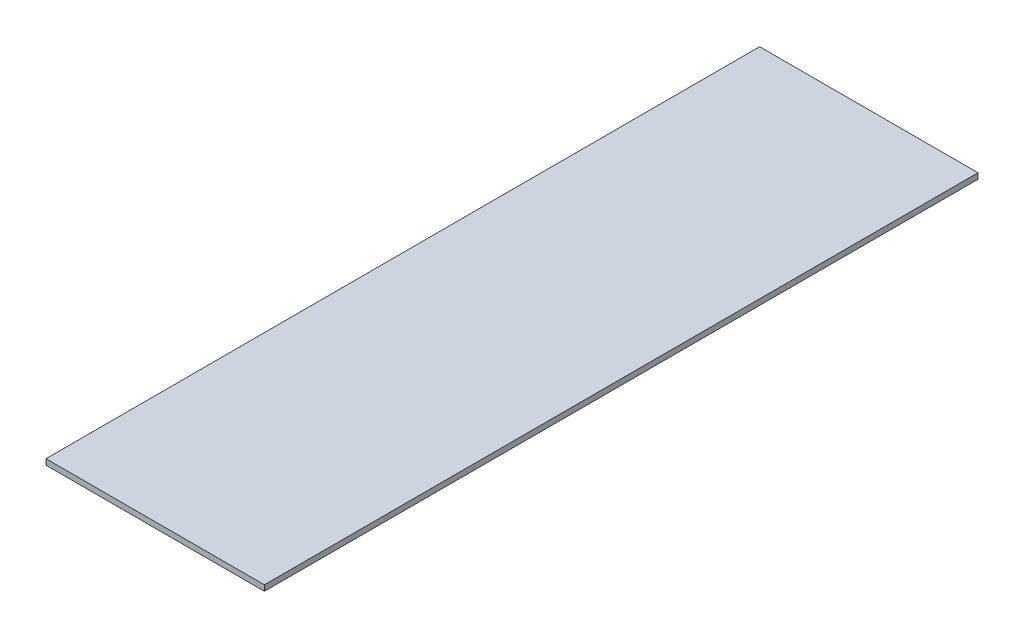
SolidWorks part; units mm, degrees
ref_plane "Front Plane" through (0, 0, 0) normal (0, 0, 1) x (1, 0, 0)
ref_plane "Top Plane" through (0, 0, 0) normal (0, 1, 0) x (1, 0, 0)
ref_plane "Right Plane" through (0, 0, 0) normal (1, 0, 0) x (0, 0, -1)
sketch "Sketch2" plane through (0, 0, 0) normal (0, 1, 0) x (1, 0, 0)
  line L1 (-87.06, 284.5) -> (87.06, 284.5)
  line L2 (-87.06, 284.5) -> (-87.06, -284.5)
  line L3 (-87.06, -284.5) -> (87.06, -284.5)
  line L4 (87.06, 284.5) -> (87.06, -284.5)
  dimension "D1" = 174.12
  dimension "D2" = 87.06
  dimension "D3" = 569
  dimension "D4" = 284.5
extrude "Boss-Extrude1" add sketch "Sketch2" along normal blind 4.5
